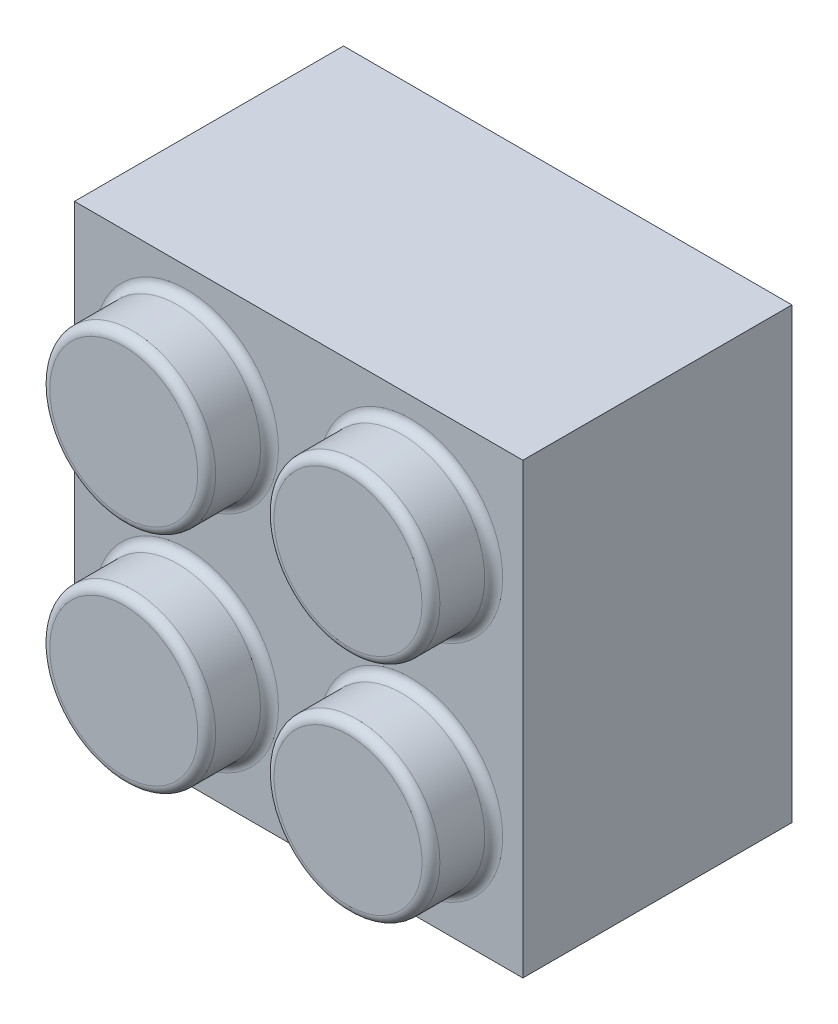
SolidWorks part; units mm, degrees
ref_plane "Plan de face" through (0, 0, 0) normal (0, 0, 1) x (1, 0, 0)
ref_plane "Plan de dessus" through (0, 0, 0) normal (0, 1, 0) x (1, 0, 0)
ref_plane "Plan de droite" through (0, 0, 0) normal (1, 0, 0) x (0, 0, -1)
sketch "Esquisse2" plane through (0, 0, 0) normal (0, 0, 1) x (1, 0, 0)
  line L0 (0, 50) -> (0, -50) construction
  line L1 (-50, 0) -> (50, 0) construction
  line L2 (50, 50) -> (-50, 50)
  line L3 (-50, 50) -> (-50, -50)
  line L4 (-50, -50) -> (50, -50)
  line L5 (50, -50) -> (50, 50)
  point P3 (51.8305, 89.8626)
  point P5 (0, 0)
  point P6 (0, 0)
  point P8 (-51.8305, 48.058)
  point P9 (-32.6541, -48.058)
  point P11 (51.8305, 0)
  point P15 (0, 0)
  point P16 (0, 0)
  point P17 (51.8305, 48.058)
  point P18 (71.0131, 0)
  point P19 (0, -63.1893)
  point P20 (50, 50)
  point P21 (-69.7947, 0)
  dimension "D1" = 100
extrude "Boss.-Extru.1" add sketch "Esquisse2" along normal blind 60
sketch "Esquisse3" plane through (0, 0, 60) normal (0, 0, 1) x (1, 0, 0)
  line L0 (0, 50) -> (0, -50) construction
  line L1 (50, 50) -> (-50, 50) construction
  line L2 (-50, -50) -> (50, -50) construction
  line L3 (50, 0) -> (-50, 0) construction
  line L4 (50, -50) -> (50, 50) construction
  line L5 (-50, 50) -> (-50, -50) construction
  line L6 (0, 0) -> (50, 50) construction
  circle A1 centre (25, 25) radius 18.5
  circle A2 centre (25, -25) radius 18.5
  circle A3 centre (-25, 25) radius 18.5
  circle A4 centre (-25, -25) radius 18.5
  dimension "D1" = 37
extrude "Boss.-Extru.2" add sketch "Esquisse3" along normal blind 14
sketch "Esquisse4" plane through (0, 0, 0) normal (0, 0, -1) x (-1, 0, 0)
  line L0 (-50, 0) -> (50, 0) construction
  line L1 (-50, -50) -> (-50, 50) construction
  line L2 (50, 50) -> (50, -50) construction
  line L3 (0, -50) -> (0, 50) construction
  line L4 (50, -50) -> (-50, -50) construction
  line L5 (-50, 50) -> (50, 50) construction
  line L6 (-42, -42) -> (-42, 42)
  line L7 (-42, 42) -> (42, 42)
  line L8 (42, 42) -> (42, -42)
  line L9 (42, -42) -> (-42, -42)
  circle A0 centre (0, 0) radius 18.5
  circle A1 centre (0, 0) radius 12
  point P20 (0, 0)
  point P21 (0, 0)
  dimension "D1" = 24
  dimension "D2" = 37
  dimension "D3" = 8
extrude "Enlèv. mat.-Extru.4" cut sketch "Esquisse4" against normal blind 50 contours L9 L8 L7 L6 A0 | A1
fillet "Congé1" radius 2 8 edges at (6.5, -25, 60) (6.5, -25, 74) (43.5, 25, 60) (43.5, 25, 74) (-43.5, 25, 60) (-43.5, 25, 74) (-6.5, -25, 60) (-6.5, -25, 74)
